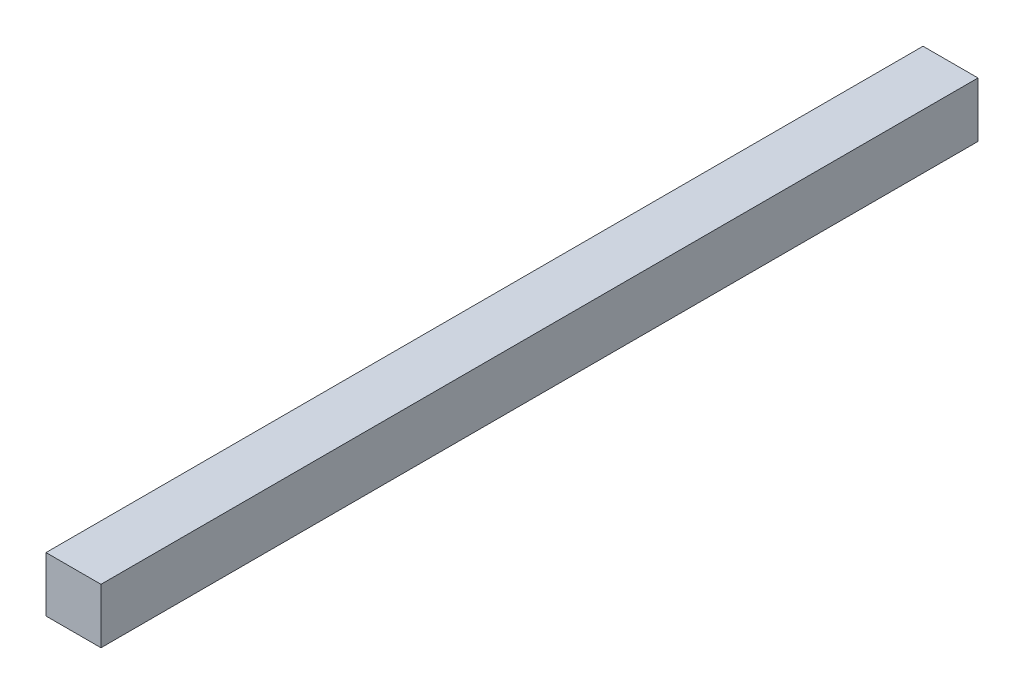
SolidWorks part; units mm, degrees
ref_plane "前视基准面" through (0, 0, 0) normal (0, 0, 1) x (1, 0, 0)
ref_plane "上视基准面" through (0, 0, 0) normal (0, 1, 0) x (1, 0, 0)
ref_plane "右视基准面" through (0, 0, 0) normal (1, 0, 0) x (0, 0, -1)
other "Configuration Table"
sketch "草图1" plane through (0, 0, 0) normal (0, 0, 1) x (1, 0, 0)
  line L1 (0, 0) -> (20, 0)
  line L2 (0, 0) -> (0, 20)
  line L3 (0, 20) -> (20, 20)
  line L4 (20, 0) -> (20, 20)
  line L5 (0, 0) -> (20, 20) construction
  line L6 (0, 20) -> (20, 0) construction
  point P4 (10, 10)
  dimension "D1" = 20
extrude "凸台-拉伸1" add sketch "草图1" along normal blind 319
